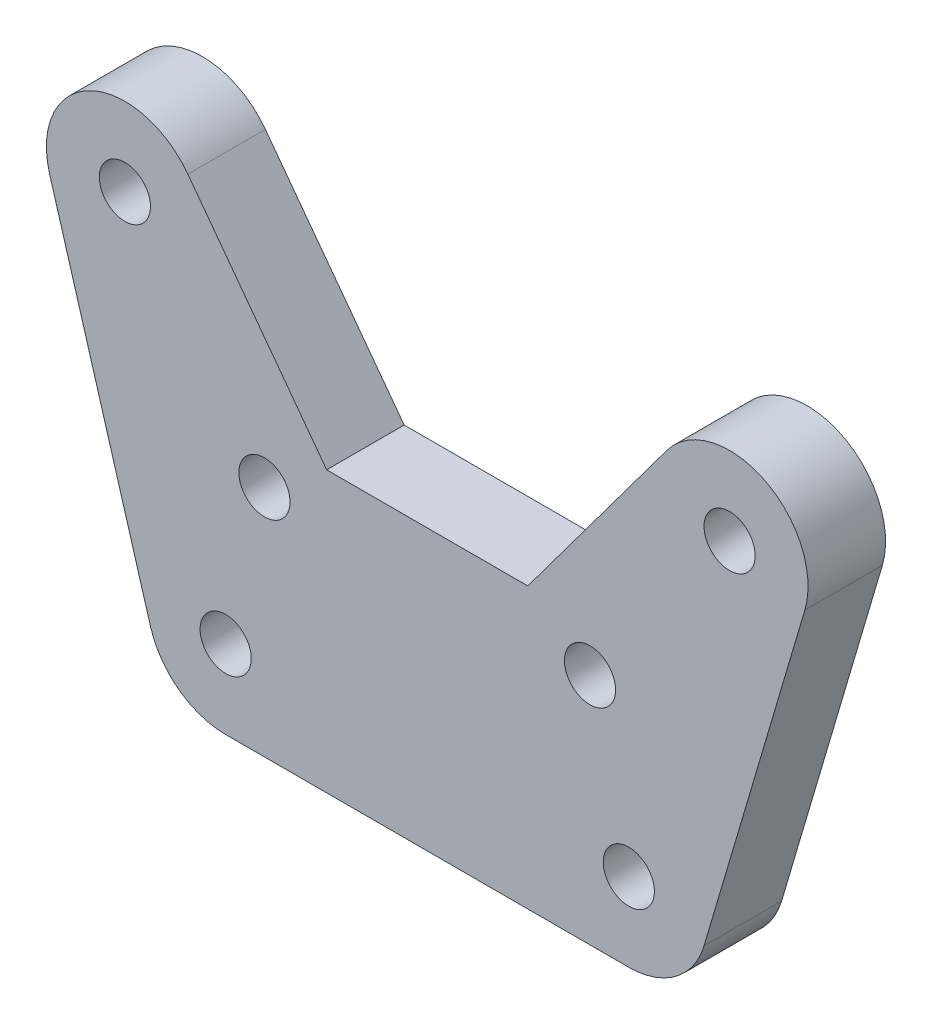
SolidWorks part; units mm, degrees
ref_plane "Płaszczyzna przednia" through (0, 0, 0) normal (0, 0, 1) x (1, 0, 0)
ref_plane "Płaszczyzna górna" through (0, 0, 0) normal (0, 1, 0) x (1, 0, 0)
ref_plane "Płaszczyzna prawa" through (0, 0, 0) normal (1, 0, 0) x (0, 0, -1)
sketch "Szkic1" plane through (0, 0, 0) normal (0, 0, 1) x (1, 0, 0)
  line L0 (-4.1597, 0) -> (15.9862, 0) construction
  line L1 (17.8537, -11.4341) -> (24.3537, 10.5659)
  line L2 (15.4387, 15.0202) -> (6.4878, 2.9837)
  line L3 (13, -15.0611) -> (-13, -15.0611)
  line L4 (6.4878, 2.9837) -> (-6.4878, 2.9837)
  line L5 (0, -55) -> (0, 55) construction
  line L6 (4.1597, 0) -> (-15.9862, 0) construction
  line L7 (-15.4387, 15.0202) -> (-6.4878, 2.9837)
  line L8 (-17.8537, -11.4341) -> (-24.3537, 10.5659)
  circle A0 centre (10.5, 0) radius 1.65
  circle A1 centre (19.5, 12) radius 1.65
  circle A2 centre (13, -10) radius 1.65
  arc A3 (13, -15.0611) -> (17.8537, -11.4341) centre (13, -10) ccw
  arc A4 (24.3537, 10.5659) -> (15.4387, 15.0202) centre (19.5, 12) ccw
  arc A6 (-24.3537, 10.5659) -> (-15.4387, 15.0202) centre (-19.5, 12) cw
  arc A7 (-13, -15.0611) -> (-17.8537, -11.4341) centre (-13, -10) cw
  circle A8 centre (-13, -10) radius 1.65
  circle A9 centre (-19.5, 12) radius 1.65
  circle A10 centre (-10.5, 0) radius 1.65
  point P18 (0, -15.0611)
  point P31 (0, 2.9837)
  dimension "D1" = 3.3
  dimension "D3" = 3.3
  dimension "D6" = 3.3
  dimension "D2" = 10.5
  dimension "D4" = 9
  dimension "D5" = 12
  dimension "D7" = 6.5
  dimension "D8" = 10
extrude "Dodanie-wyciągnięcie1" add sketch "Szkic1" along normal blind 5
